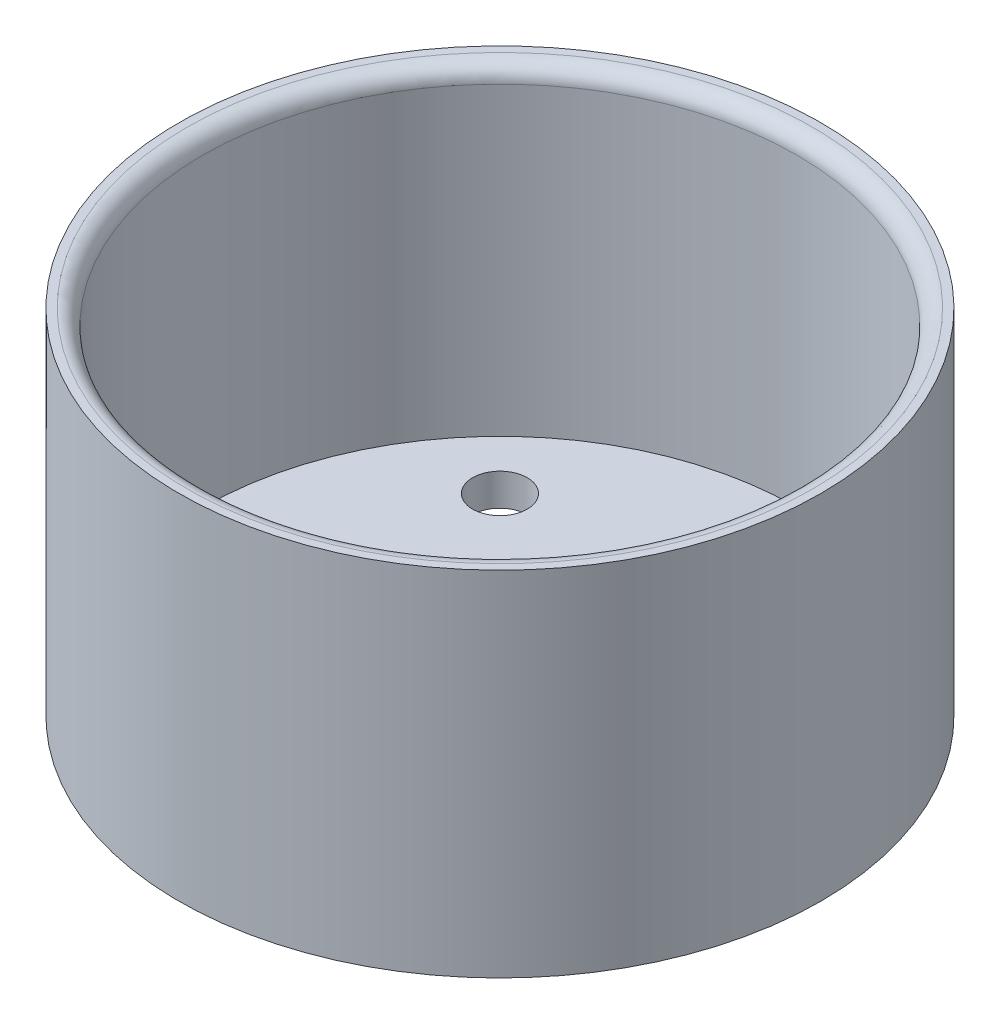
SolidWorks part; units mm, degrees
ref_plane "前视基准面" through (0, 0, 0) normal (0, 0, 1) x (1, 0, 0)
ref_plane "上视基准面" through (0, 0, 0) normal (0, 1, 0) x (1, 0, 0)
ref_plane "右视基准面" through (0, 0, 0) normal (1, 0, 0) x (0, 0, -1)
sketch "草图3" plane through (0, 0, 0) normal (0, 0, 1) x (1, 0, 0)
  line L1 (0, 0) -> (19, 0)
  line L2 (0, 0) -> (0, 2)
  line L3 (0, 2) -> (18.5, 2)
  line L4 (20, 1) -> (20, 2)
  line L6 (20, 2) -> (20, 22)
  line L7 (20, 22) -> (19.5, 22)
  line L8 (18.5, 2) -> (18.5, 21)
  line L9 (0, 2) -> (18.5, 2)
  line L10 (0, 2) -> (0, 0)
  line L11 (0, 0) -> (20, 0)
  line L12 (20, 1) -> (20, 0)
  arc A1 (19.5, 22) -> (18.5, 21) centre (19.5, 21) ccw
  dimension "D1" = 2
  dimension "D2" = 1
  dimension "D3" = 20
  dimension "D4" = 20
  dimension "D5" = 1.5
revolve "旋转1" add sketch "草图3" angle 360 about L2
sketch "草图4" plane through (0, 2, 0) normal (0, 1, 0) x (1, 0, 0)
  line L1 (10, -10) -> (-10, -10)
  line L2 (10, -10) -> (10, 10)
  line L3 (10, 10) -> (-10, 10)
  line L4 (-10, -10) -> (-10, 10)
  line L5 (10, -10) -> (-10, 10) construction
  line L6 (10, 10) -> (-10, -10) construction
  circle A0 centre (10, -10) radius 1.7
  circle A1 centre (-10, -10) radius 1.7
  circle A2 centre (-10, 10) radius 1.7
  circle A3 centre (10, 10) radius 1.7
  point P0 (0, 0)
  point P16 (0, 0)
extrude "切除-拉伸1" cut sketch "草图4" against normal blind 10 contours L1 A0 L2 | L2 A0 L1 | L1 A1 L4 | L4 A1 L1 | L3 A2 L4 | L4 A2 L3 | L3 A3 L2 | L2 A3 L3
